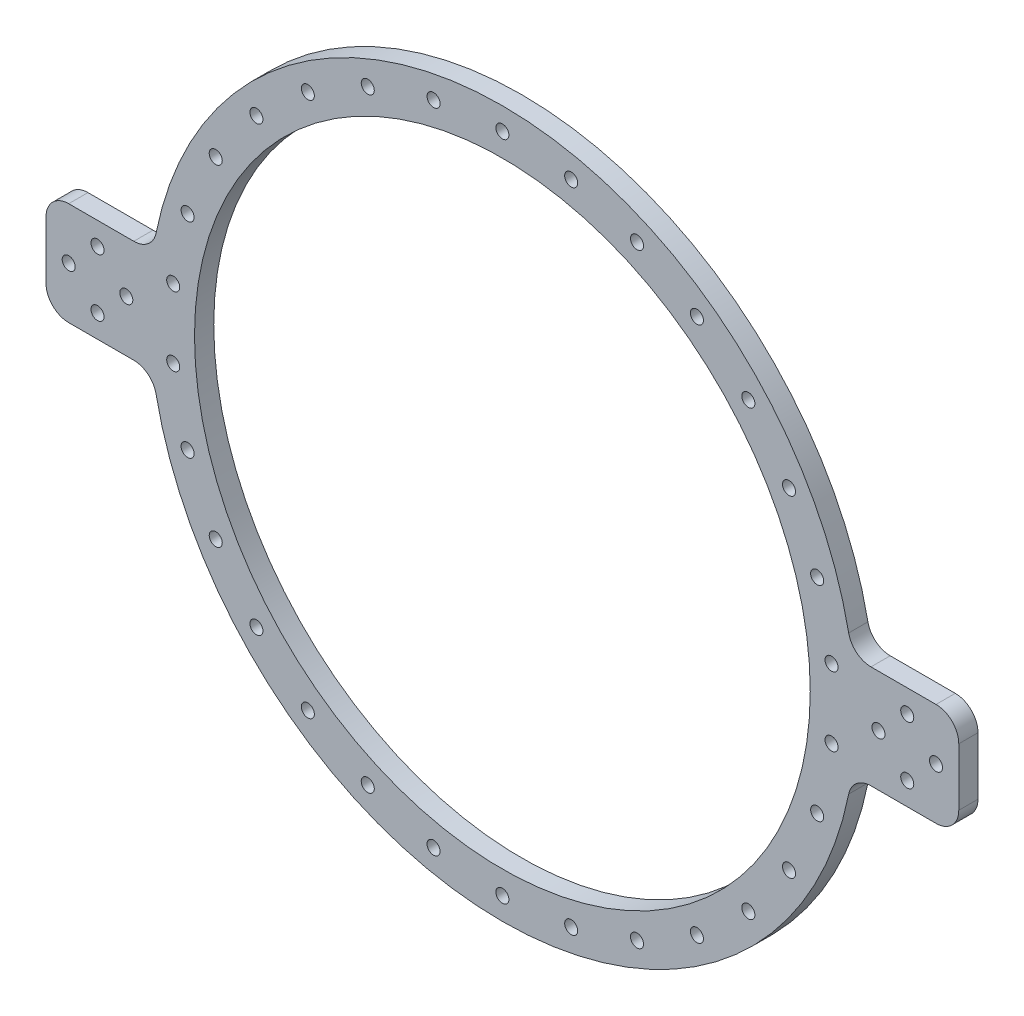
SolidWorks part; units mm, degrees
material "PC High Viscosity"
ref_plane "Front Plane" through (0, 0, 0) normal (0, 0, 1) x (1, 0, 0)
ref_plane "Top Plane" through (0, 0, 0) normal (0, 1, 0) x (1, 0, 0)
ref_plane "Right Plane" through (0, 0, 0) normal (1, 0, 0) x (0, 0, -1)
sketch "Sketch1" plane through (0, 0, 0) normal (0, 0, 1) x (1, 0, 0)
  line L0 (109.1, 0) -> (101.6, 0) construction
  line L1 (109.1, 0) -> (116.6, 0) construction
  line L2 (115.3265, 17) -> (143.1, 17)
  line L3 (150.6, 9.5) -> (150.6, -9.5)
  line L4 (143.1, -17) -> (115.3265, -17)
  line L5 (0, 0) -> (204.7679, 0) construction
  line L6 (0, 0) -> (0, 58.5097) construction
  line L7 (133.6, 9.5) -> (143.1, 0) construction
  line L8 (143.1, 0) -> (133.6, -9.5) construction
  line L9 (133.6, -9.5) -> (124.1, 0) construction
  line L10 (124.1, 0) -> (133.6, 9.5) construction
  line L11 (133.6, 9.5) -> (133.6, 17) construction
  line L12 (124.1, 0) -> (116.6, 0) construction
  line L13 (-115.3265, 17) -> (-143.1, 17)
  line L14 (-150.6, 9.5) -> (-150.6, -9.5)
  line L15 (-143.1, -17) -> (-115.3265, -17)
  line L16 (0, 101.6) -> (0, 116.5727) construction
  circle A0 centre (0, 0) radius 101.6
  arc A1 (115.3265, 17) -> (-115.3265, 17) centre (0, 0) ccw
  arc A33 (143.1, 17) -> (150.6, 9.5) centre (143.1, 9.5) cw
  arc A34 (150.6, -9.5) -> (143.1, -17) centre (143.1, -9.5) cw
  circle A35 centre (133.6, 9.5) radius 2.1525
  circle A36 centre (133.6, -9.5) radius 2.1525
  circle A37 centre (143.1, 0) radius 2.1525
  circle A38 centre (124.1, 0) radius 2.1525
  arc A39 (115.3265, -17) -> (116.5727, 0) centre (0, 0) ccw construction
  arc A40 (-143.1, 17) -> (-150.6, 9.5) centre (-143.1, 9.5) ccw
  arc A41 (-150.6, -9.5) -> (-143.1, -17) centre (-143.1, -9.5) ccw
  circle A42 centre (-143.1, 0) radius 2.1525
  circle A43 centre (-133.6, -9.5) radius 2.1525
  circle A44 centre (-124.1, 0) radius 2.1525
  circle A45 centre (-133.6, 9.5) radius 2.1525
  arc A46 (-115.3265, -17) -> (115.3265, -17) centre (0, 0) ccw
  circle A48 centre (0, 109.22) radius 2.1525
  circle A49 centre (22.7081, 106.8333) radius 2.1525
  circle A50 centre (44.4238, 99.7774) radius 2.1525
  circle A51 centre (64.1979, 88.3608) radius 2.1525
  circle A52 centre (81.1663, 73.0824) radius 2.1525
  circle A53 centre (94.5873, 54.61) radius 2.1525
  circle A54 centre (103.8744, 33.7508) radius 2.1525
  circle A55 centre (108.6217, 11.4166) radius 2.1525
  circle A56 centre (108.6217, -11.4166) radius 2.1525
  circle A57 centre (103.8744, -33.7508) radius 2.1525
  circle A58 centre (94.5873, -54.61) radius 2.1525
  circle A59 centre (81.1663, -73.0824) radius 2.1525
  circle A60 centre (64.1979, -88.3608) radius 2.1525
  circle A61 centre (44.4238, -99.7774) radius 2.1525
  circle A62 centre (22.7081, -106.8333) radius 2.1525
  circle A63 centre (0, -109.22) radius 2.1525
  circle A64 centre (-22.7081, -106.8333) radius 2.1525
  circle A65 centre (-44.4238, -99.7774) radius 2.1525
  circle A66 centre (-64.1979, -88.3608) radius 2.1525
  circle A67 centre (-81.1663, -73.0824) radius 2.1525
  circle A68 centre (-94.5873, -54.61) radius 2.1525
  circle A69 centre (-103.8744, -33.7508) radius 2.1525
  circle A70 centre (-108.6217, -11.4166) radius 2.1525
  circle A71 centre (-108.6217, 11.4166) radius 2.1525
  circle A72 centre (-103.8744, 33.7508) radius 2.1525
  circle A73 centre (-94.5873, 54.61) radius 2.1525
  circle A74 centre (-81.1663, 73.0824) radius 2.1525
  circle A75 centre (-64.1979, 88.3608) radius 2.1525
  circle A76 centre (-44.4238, 99.7774) radius 2.1525
  circle A77 centre (-22.7081, 106.8333) radius 2.1525
  circle A78 centre (0, 0) radius 109.22 construction
  point P15 (0, 109.22)
  point P112 (0, 0)
  dimension "D1" = 203.2
  dimension "D2" = 109.22
  dimension "D3" = 4.305
  dimension "D6" = 19
  dimension "D7" = 4.305
  dimension "D11" = 7.5
  dimension "D13" = 116.5727
  dimension "D14" = 30
  dimension "D4" = 7.5
  dimension "D5" = 7.5
  dimension "D8" = 19
  dimension "D9" = 7.5
  dimension "D10" = 7.5
  dimension "D12" = 7.5
extrude "Boss-Extrude1" add sketch "Sketch1" along normal blind 6.35
fillet "Fillet1" radius 7.5 4 edges at (115.3265, -17, 3.175) (115.3265, 17, 3.175) (-115.3265, -17, 3.175) (-115.3265, 17, 3.175)
